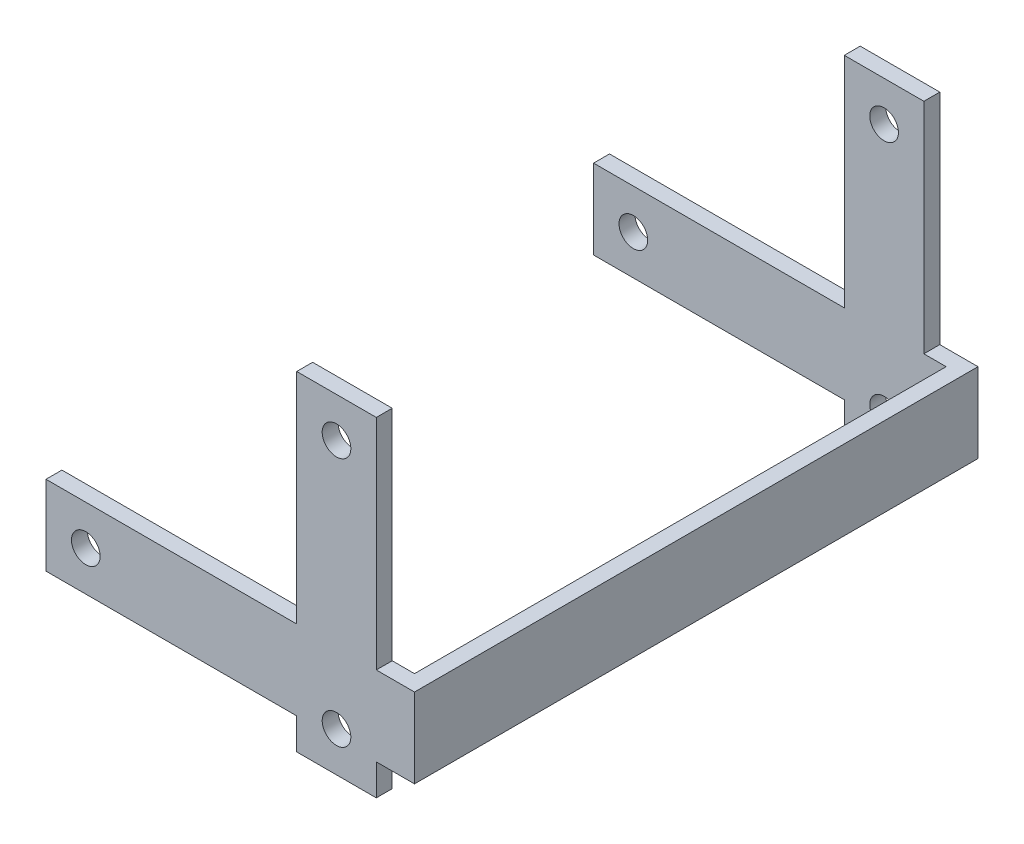
SolidWorks part; units mm, degrees
material "AISI 316 Stainless Steel Sheet (SS)"
ref_plane "Front Plane" through (0, 0, 0) normal (0, 0, 1) x (1, 0, 0)
ref_plane "Top Plane" through (0, 0, 0) normal (0, 1, 0) x (1, 0, 0)
ref_plane "Right Plane" through (0, 0, 0) normal (1, 0, 0) x (0, 0, -1)
sketch "Sketch1" plane through (0, 0, 0) normal (0, 0, 1) x (1, 0, 0)
  line L0 (0, 0) -> (-78.75, 0)
  line L1 (-78.75, 0) -> (-78.75, -25)
  line L2 (-78.75, -25) -> (0, -25)
  line L3 (0, -25) -> (0, -34.8)
  line L4 (0, -34.8) -> (25, -34.8)
  line L5 (25, -34.8) -> (25, -25)
  line L6 (25, -25) -> (37, -25)
  line L7 (37, -25) -> (37, 0)
  line L8 (37, 0) -> (25, 0)
  line L9 (25, 0) -> (25, 68.7)
  line L10 (25, 68.7) -> (0, 68.7)
  line L11 (0, 68.7) -> (0, 0)
  circle A0 centre (-66.25, -12.5) radius 4.5
  circle A1 centre (12.5, -22.3) radius 4.5
  circle A2 centre (12.5, 56.2) radius 4.5
  dimension "D2" = 9
  dimension "D9" = 9
  dimension "D10" = 9
  dimension "D11" = 12.5
  dimension "D1" = 78.75
  dimension "D3" = 25
  dimension "D4" = 25
  dimension "D5" = 25
  dimension "D6" = 68.7
  dimension "D7" = 12.5
  dimension "D8" = 115.75
  dimension "D12" = 12.5
  dimension "D13" = 12.5
  dimension "D14" = 12.5
  dimension "D15" = 78.5
  dimension "D16" = 12.5
extrude "Boss-Extrude1" add sketch "Sketch1" along normal blind 5
sketch "Sketch2" plane through (0, 0, 0) normal (0, 0, -1) x (-1, 0, 0)
  line L0 (-37, 0) -> (-37, -25)
  line L1 (-37, 0) -> (-32, 0)
  line L2 (-37, -25) -> (-32, -25)
  line L3 (-32, 0) -> (-32, -25)
  dimension "D1" = 5
extrude "Boss-Extrude2" add sketch "Sketch2" along normal blind 83.5
ref_plane "Plane1" through (0, 0, -83.5) normal (0, 0, -1) x (-1, 0, 0)
mirror "Mirror5" about plane through (0, 0, -83.5) normal (0, 0, -1) of bodies 103
